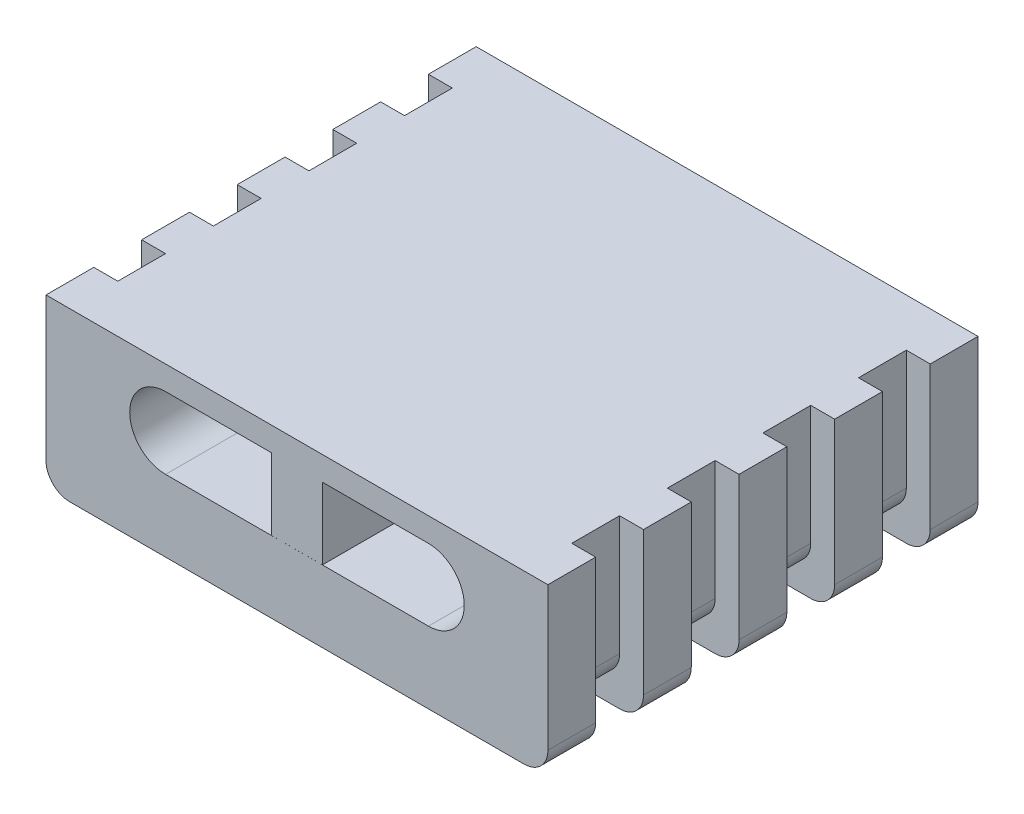
SolidWorks part; units mm, degrees
material "Gray Cast Iron"
ref_plane "Front" through (0, 0, 0) normal (0, 0, 1) x (1, 0, 0)
ref_plane "Top" through (0, 0, 0) normal (0, 1, 0) x (1, 0, 0)
ref_plane "Right" through (0, 0, 0) normal (1, 0, 0) x (0, 0, -1)
sketch "Sketch2" plane through (0, 0, 0) normal (0, 0, 1) x (1, 0, 0)
  line L1 (-10.5, 3.5) -> (10.5, 3.5)
  line L2 (-10.5, 3.5) -> (-10.5, -3.5)
  line L3 (-10.5, -3.5) -> (10.5, -3.5)
  line L4 (10.5, 3.5) -> (10.5, -3.5)
  line L5 (-10.5, 3.5) -> (10.5, -3.5) construction
  line L6 (-10.5, -3.5) -> (10.5, 3.5) construction
  point P0 (0, 0)
  dimension "D1" = 7
  dimension "D2" = 21
extrude "Boss-Extrude1" add sketch "Sketch2" along normal blind 2
sketch "Sketch3" plane through (0, 0, 2) normal (0, 0, 1) x (1, 0, 0)
  line L0 (-9.5, 3.5) -> (-9.5, -2.5)
  line L1 (10.5, 3.5) -> (-10.5, 3.5) construction
  line L2 (-9.5, -2.5) -> (9.5, -2.5)
  line L3 (9.5, -2.5) -> (9.5, 3.5)
  line L4 (9.5, 3.5) -> (-9.5, 3.5)
  line L5 (-10.5, 3.5) -> (-10.5, -3.5) construction
  line L6 (10.5, -3.5) -> (10.5, 3.5) construction
  line L7 (-10.5, -3.5) -> (10.5, -3.5) construction
  dimension "D1" = 1
  dimension "D2" = 1
  dimension "D3" = 1
extrude "Boss-Extrude2" add sketch "Sketch3" along normal blind 2
sketch "Sketch4" plane through (0, 0, 4) normal (0, 0, 1) x (1, 0, 0)
  line L1 (10.5, 3.5) -> (-10.5, 3.5)
  line L2 (10.5, 3.5) -> (10.5, -3.5)
  line L3 (10.5, -3.5) -> (-10.5, -3.5)
  line L4 (-10.5, 3.5) -> (-10.5, -3.5)
  line L5 (10.5, 3.5) -> (-10.5, -3.5) construction
  line L6 (10.5, -3.5) -> (-10.5, 3.5) construction
  point P0 (0, 0)
extrude "Boss-Extrude3" add sketch "Sketch4" along normal blind 2
sketch "Sketch5" plane through (0, 0, 6) normal (0, 0, 1) x (1, 0, 0)
  line L0 (-9.5, 3.5) -> (-9.5, -2.5)
  line L1 (-9.5, -2.5) -> (9.5, -2.5) construction
  line L2 (-9.5, 3.5) -> (-9.5, -2.5) construction
  line L3 (-9.5, -2.5) -> (9.5, -2.5)
  line L4 (9.5, -2.5) -> (9.5, 3.5)
  line L5 (9.5, 3.5) -> (-9.5, 3.5)
extrude "Boss-Extrude4" add sketch "Sketch5" along normal blind 2
sketch "Sketch6" plane through (0, 0, 8) normal (0, 0, 1) x (1, 0, 0)
  line L0 (-10.5, -3.5) -> (10.5, -3.5) construction
  line L1 (-10.5, 3.5) -> (10.5, 3.5)
  line L2 (-10.5, 3.5) -> (-10.5, -3.5)
  line L3 (-10.5, -3.5) -> (10.5, -3.5)
  line L4 (10.5, 3.5) -> (10.5, -3.5)
  line L5 (-10.5, 3.5) -> (10.5, -3.5) construction
  line L6 (-10.5, -3.5) -> (10.5, 3.5) construction
  point P0 (0, 0)
extrude "Boss-Extrude5" add sketch "Sketch6" along normal blind 2
sketch "Sketch7" plane through (0, 0, 10) normal (0, 0, 1) x (1, 0, 0)
  line L1 (-9.5, -2.5) -> (9.5, -2.5)
  line L2 (-9.5, -2.5) -> (-9.5, 3.5)
  line L3 (-9.5, 3.5) -> (9.5, 3.5)
  line L4 (9.5, -2.5) -> (9.5, 3.5)
  line L5 (0, 3.5) -> (0, -2.5) construction
  line L6 (-9.5, 0.5) -> (9.5, 0.5) construction
  point P156 (0, 0.5)
extrude "Boss-Extrude6" add sketch "Sketch7" along normal blind 2
sketch "Sketch8" plane through (0, 0, 12) normal (0, 0, 1) x (1, 0, 0)
  line L0 (10.5, 3.5) -> (9.5, 3.5) construction
  line L1 (-10.5, -3.5) -> (10.5, -3.5)
  line L2 (-10.5, -3.5) -> (-10.5, 3.5)
  line L3 (-10.5, 3.5) -> (10.5, 3.5)
  line L4 (10.5, -3.5) -> (10.5, 3.5)
  line L5 (0, 3.5) -> (0, -3.5) construction
  line L6 (-10.5, 0) -> (10.5, 0) construction
  line L7 (10.5, -3.5) -> (10.5, 3.5) construction
  point P224 (0, 0)
extrude "Boss-Extrude7" add sketch "Sketch8" along normal blind 2
fillet "Fillet1" radius 1 14 edges at (10.5, -3.5, 1) (9.5, -2.5, 3) (10.5, -3.5, 5) (9.5, -2.5, 7) (10.5, -3.5, 9) (9.5, -2.5, 11) (10.5, -3.5, 13) (-10.5, -3.5, 1) (-9.5, -2.5, 3) (-10.5, -3.5, 5) (-9.5, -2.5, 7) (-10.5, -3.5, 9) (-9.5, -2.5, 11) (-10.5, -3.5, 13)
sketch "Sketch12" plane through (0, 0, 0) normal (0, 0, -1) x (-1, 0, 0)
  line L0 (-5.5, 1) -> (5.5, 1) construction
  line L1 (9.5, -3.5) -> (-9.5, -3.5) construction
  line L2 (-5.5, 1) -> (5.5, 1) construction
  line L3 (-5.5, 2.5) -> (5.5, 2.5)
  line L4 (-5.5, -0.5) -> (5.5, -0.5)
  arc A0 (-5.5, 2.5) -> (-5.5, -0.5) centre (-5.5, 1) ccw
  arc A1 (5.5, -0.5) -> (5.5, 2.5) centre (5.5, 1) ccw
  point P5 (0, 1)
  dimension "D1" = 4.5
  dimension "D2" = 5.5
  dimension "D3" = 5.5
extrude "Cut-Extrude2" cut sketch "Sketch12" against normal blind 14
sketch "Sketch13" plane through (0, 0, 0) normal (0, 0, -1) x (-1, 0, 0)
  line L1 (-5.5, -0.5) -> (5.5, -0.5) construction
  line L2 (0, -0.5) -> (0, 2.6401) construction
  line L3 (-1.0643, 2.6401) -> (1.0643, 2.6401)
  line L4 (-1.0643, 2.6401) -> (-1.0643, -0.5)
  line L5 (-1.0643, -0.5) -> (1.0643, -0.5)
  line L6 (1.0643, 2.6401) -> (1.0643, -0.5)
  line L7 (-1.0643, 2.6401) -> (1.0643, -0.5) construction
  line L8 (-1.0643, -0.5) -> (1.0643, 2.6401) construction
  point P0 (0, 1.0701)
extrude "Boss-Extrude9" add sketch "Sketch13" against normal blind 14
sketch "Sketch14" plane through (0, 0, 14) normal (0, 0, 1) x (1, 0, 0)
  line L0 (10.5, 3.5) -> (-10.5, 3.5) construction
  line L1 (9.5, 3.5) -> (-9.5, 3.5)
  line L2 (9.5, 3.5) -> (9.5, -2.5)
  line L3 (9.5, -2.5) -> (-9.5, -2.5)
  line L4 (-9.5, 3.5) -> (-9.5, -2.5)
  line L5 (0, -2.5) -> (0, 3.5) construction
  line L6 (9.5, 0.5) -> (-9.5, 0.5) construction
  line L7 (-9.5, -3.5) -> (9.5, -3.5) construction
  line L8 (-10.5, 3.5) -> (-10.5, -2.5) construction
  line L9 (10.5, -2.5) -> (10.5, 3.5) construction
  point P600 (0, 0.5)
  dimension "D1" = 1
  dimension "D2" = 1
  dimension "D3" = 1
extrude "Boss-Extrude10" add sketch "Sketch14" along normal blind 2
sketch "Sketch15" plane through (0, 0, 16) normal (0, 0, 1) x (1, 0, 0)
  line L1 (10.5, 3.5) -> (-10.5038, 3.5)
  line L2 (10.5, 3.5) -> (10.5, -3.5019)
  line L3 (10.5, -3.5019) -> (-10.5038, -3.5019)
  line L4 (-10.5038, 3.5) -> (-10.5038, -3.5019)
  line L5 (-0.0019, -3.5019) -> (-0.0019, 3.5) construction
  line L6 (10.5, -0.0009) -> (-10.5038, -0.0009) construction
  point P284 (-0.0019, -0.0009)
extrude "Boss-Extrude11" add sketch "Sketch15" along normal blind 2
fillet "Fillet2" radius 1 4 edges at (-9.5, -2.5, 15) (-10.5038, -3.5019, 17) (10.5, -3.5019, 17) (9.5, -2.5, 15)
sketch "Sketch16" plane through (0, 0, 18) normal (0, 0, 1) x (1, 0, 0)
  line L0 (5.5, 0.9981) -> (-5.5, 0.9981) construction
  line L1 (-9.5038, -3.5019) -> (9.5, -3.5019) construction
  line L2 (5.5, 0.9981) -> (-5.5, 0.9981) construction
  line L3 (5.5, -0.5019) -> (-5.5, -0.5019)
  line L4 (5.5, 2.4981) -> (-5.5, 2.4981)
  arc A0 (5.5, -0.5019) -> (5.5, 2.4981) centre (5.5, 0.9981) ccw
  arc A1 (-5.5, 2.4981) -> (-5.5, -0.5019) centre (-5.5, 0.9981) ccw
  point P5 (0, 0.9981)
  dimension "D1" = 4.5
  dimension "D2" = 5.5
  dimension "D3" = 5.5
extrude "Cut-Extrude4" cut sketch "Sketch16" against normal blind 4
sketch "Sketch17" plane through (0, 0, 18) normal (0, 0, 1) x (1, 0, 0)
  line L1 (1.0643, -0.5) -> (-1.0643, -0.5)
  line L2 (1.0643, -0.5) -> (1.0643, 2.4981)
  line L3 (1.0643, 2.4981) -> (-1.0643, 2.4981)
  line L4 (-1.0643, -0.5) -> (-1.0643, 2.4981)
  line L5 (0, 2.4981) -> (0, -0.5) construction
  line L6 (1.0643, 0.9991) -> (-1.0643, 0.9991) construction
  point P228 (0, 0.9991)
extrude "Boss-Extrude12" add sketch "Sketch17" against normal blind 4
